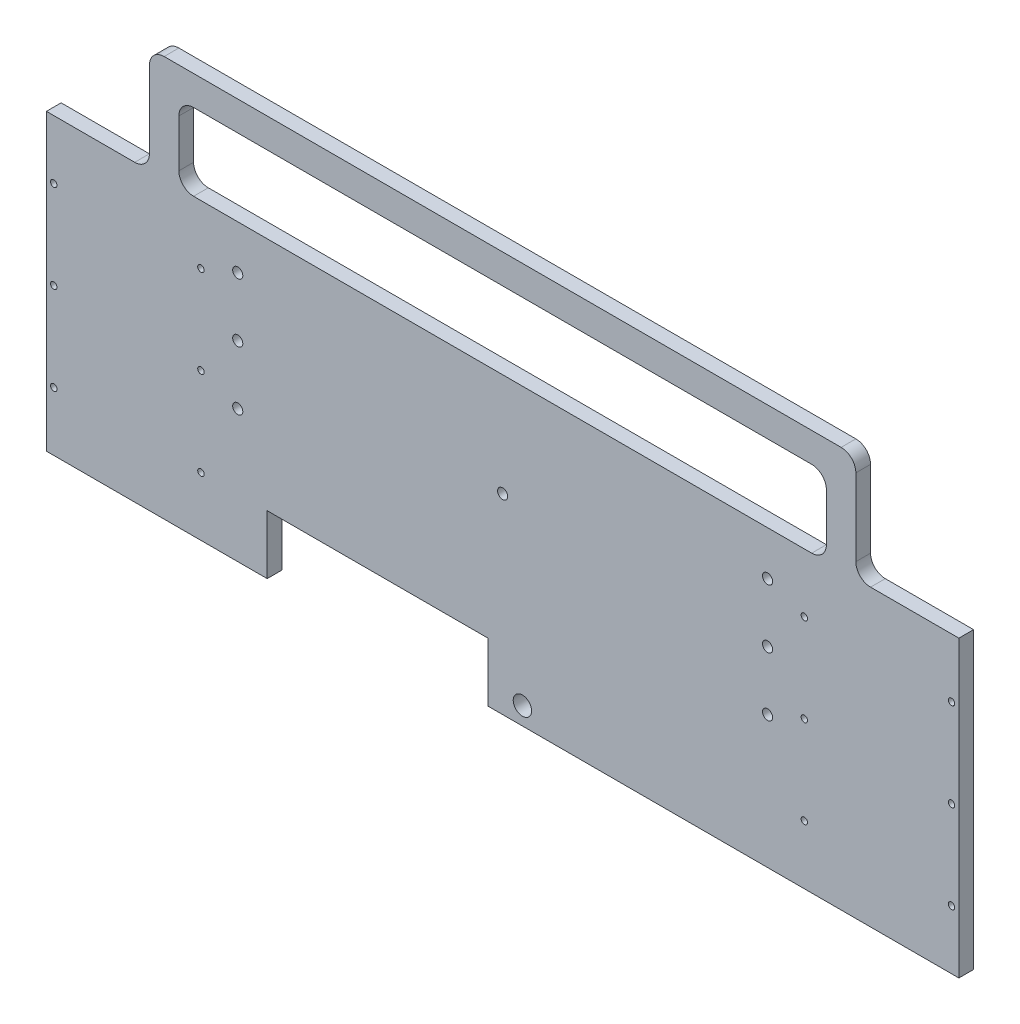
SolidWorks part; units mm, degrees
material "6061-T6 (SS)"
ref_plane "Front Plane" through (0, 0, 0) normal (0, 0, 1) x (1, 0, 0)
ref_plane "Top Plane" through (0, 0, 0) normal (0, 1, 0) x (1, 0, 0)
ref_plane "Right Plane" through (0, 0, 0) normal (1, 0, 0) x (0, 0, -1)
sketch "Sketch1" plane through (0, 0, 0) normal (0, 0, 1) x (1, 0, 0)
  line L1 (-196.85, 63.5) -> (196.85, 63.5)
  line L2 (-196.85, 63.5) -> (-196.85, -63.5)
  line L3 (-196.85, -63.5) -> (196.85, -63.5)
  line L4 (196.85, 63.5) -> (196.85, -63.5)
  line L5 (-196.85, 63.5) -> (196.85, -63.5) construction
  line L6 (-196.85, -63.5) -> (196.85, 63.5) construction
  point P0 (0, 0)
  dimension "D1" = 127
  dimension "D2" = 393.7
extrude "Boss-Extrude1" add sketch "Sketch1" along normal blind 6.35
sketch "Sketch2" plane through (0, 0, 6.35) normal (0, 0, 1) x (1, 0, 0)
  line L0 (196.85, -63.5) -> (196.85, 63.5) construction
  line L1 (-91.44, 27.94) -> (91.44, 27.94) construction
  line L2 (-91.44, 27.94) -> (-91.44, -27.94) construction
  line L3 (-91.44, -27.94) -> (91.44, -27.94) construction
  line L4 (91.44, 27.94) -> (91.44, -27.94) construction
  line L5 (-91.44, 27.94) -> (91.44, -27.94) construction
  line L6 (-91.44, -27.94) -> (91.44, 27.94) construction
  line L7 (192.278, -48.26) -> (-192.278, -48.26) construction
  line L8 (192.278, -48.26) -> (192.278, -11.43) construction
  line L9 (192.278, -11.43) -> (-192.278, -11.43) construction
  line L10 (-192.278, -48.26) -> (-192.278, -11.43) construction
  line L11 (192.278, -48.26) -> (-192.278, -11.43) construction
  line L12 (192.278, -11.43) -> (-192.278, -48.26) construction
  line L13 (-196.85, -63.5) -> (196.85, -63.5) construction
  point P0 (0, 0)
  point P6 (0, -29.845)
  point P13 (91.44, 0)
  point P19 (-91.44, 0)
  dimension "D1" = 182.88
  dimension "D2" = 55.88
  dimension "D3" = 4.572
  dimension "D4" = 36.83
  dimension "D5" = 15.24
sketch "Sketch10" plane through (0, 0, 6.35) normal (0, 0, 1) x (1, 0, 0)
  line L0 (196.85, 63.5) -> (-196.85, 63.5) construction
  line L1 (-152.4, 63.5) -> (-139.7, 63.5)
  line L2 (-152.4, 63.5) -> (-152.4, 109.383)
  line L3 (-152.4, 109.383) -> (-146.05, 109.383)
  line L4 (-139.7, 63.5) -> (-139.7, 96.683)
  line L5 (-196.85, 63.5) -> (-196.85, -63.5) construction
  line L6 (-152.4, 109.383) -> (152.4, 109.383)
  line L7 (-152.4, 109.383) -> (-152.4, 96.683)
  line L8 (-139.7, 96.683) -> (139.7, 96.683)
  line L9 (0, 109.383) -> (0, 96.683)
  line L10 (139.7, 63.5) -> (139.7, 96.683)
  line L11 (152.4, 63.5) -> (139.7, 63.5)
  line L12 (152.4, 63.5) -> (152.4, 109.383)
  line M12 (196.85, 63.5) -> (-196.85, 63.5)
  dimension "D1" = 12.7
  dimension "D2" = 12.7
  dimension "D3" = 152.4
  dimension "D4" = 44.45
extrude "Boss-Extrude2" add sketch "Sketch10" against normal blind 6.35 contours L9 L6 L3 L2 L4 L8 M12 | L12 L6 L9 L8 L10 M12
fillet "Fillet1" radius 6.35 8 edges at (152.4, 109.383, 3.175) (-152.4, 109.383, 3.175) (-152.4, 63.5, 3.175) (152.4, 63.5, 3.175) (139.7, 96.683, 3.175) (139.7, 63.5, 3.175) (-139.7, 63.5, 3.175) (-139.7, 96.683, 3.175)
sketch "Sketch9" plane through (0, 0, 6.35) normal (0, 0, 1) x (1, 0, 0)
  line L103 (-196.85, -63.5) -> (196.85, -63.5) construction
  point P113 (0, -63.5)
sketch "Sketch11" plane through (0, 0, 6.35) normal (0, 0, 1) x (1, 0, 0)
  line L0 (-196.85, -63.5) -> (196.85, -63.5) construction
  line L1 (-101.6, -63.5) -> (-6.35, -63.5)
  line L2 (-101.6, -63.5) -> (-101.6, -38.1)
  line L3 (-101.6, -38.1) -> (-6.35, -38.1)
  line L4 (-6.35, -63.5) -> (-6.35, -38.1)
  line L5 (-196.85, 63.5) -> (-196.85, -63.5) construction
  line L6 (196.85, -63.5) -> (196.85, 63.5) construction
  dimension "D1" = 25.4
  dimension "D2" = 95.25
  dimension "D3" = 203.2
extrude "Cut-Extrude1" cut sketch "Sketch11" against normal through all
sketch "Sketch12" plane through (0, 0, 6.35) normal (0, 0, 1) x (1, 0, 0)
  line L0 (-6.35, -63.5) -> (-6.35, -38.1) construction
  line L1 (-6.35, -63.5) -> (196.85, -63.5) construction
  point P0 (8.5349, -55.88)
  dimension "D1" = 14.8849
  dimension "D2" = 7.62
hole_wizard "5/16 (0.3125) Diameter Hole1" positions "Sketch13" profile "Sketch14" hole size "5/16" standard "ANSI Inch" end condition through all
sketch "Sketch13" plane through (0, 0, 6.35) normal (0, 0, 1) x (1, 0, 0)
  point P0 (8.5349, -55.88)
sketch "Sketch14" plane through (8.5349, -55.88, 6.35) normal (1, 0, 0) x (0, -1, 0)
  line L0 (0, 0) -> (0, 6.35)
  line L1 (0, 6.35) -> (3.9687, 6.35)
  line L2 (3.9687, 6.35) -> (3.9687, 0)
  line L5 (3.9687, 0) -> (0, 0)
  line L11 (0, -6.35) -> (0, 107.95) construction
  dimension "Thru Hole Dia." = 7.9375
  dimension "Thru Hole Depth" = 6.35
sketch "Sketch15" plane through (0, 0, 6.35) normal (0, 0, 1) x (1, 0, 0)
  line L1 (-196.85, 63.5) -> (-196.85, -63.5) construction
  line L2 (-196.85, -63.5) -> (-101.6, -63.5) construction
  line L3 (196.85, -63.5) -> (196.85, 63.5) construction
  line L4 (-6.35, -63.5) -> (196.85, -63.5) construction
  point P0 (-114.3, -57.15)
  point P1 (-114.3, -31.75)
  point P2 (-114.3, -6.35)
  point P3 (-114.3, 19.05)
  point P8 (-114.3, 44.45)
  point P9 (114.3, -57.15)
  point P11 (114.3, -31.75)
  point P12 (114.3, -6.35)
  point P13 (114.3, 19.05)
  point P14 (114.3, 44.45)
  dimension "D1" = 82.55
  dimension "D2" = 6.35
  dimension "D3" = 25.4
  dimension "D4" = 25.4
  dimension "D5" = 25.4
  dimension "D6" = 25.4
  dimension "D7" = 25.4
  dimension "D8" = 25.4
  dimension "D9" = 25.4
  dimension "D10" = 25.4
  dimension "D11" = 82.55
  dimension "D12" = 6.35
hole_wizard "11/64 (0.17188) Diameter Hole1" positions "Sketch16" profile "Sketch17" hole size "11/64" standard "ANSI Inch" end condition through all
sketch "Sketch16" plane through (0, 0, 6.35) normal (0, 0, 1) x (1, 0, 0)
  point P0 (-114.3, 44.45)
  point P3 (-114.3, 19.05)
  point P6 (-114.3, -6.35)
  point P12 (114.3, 44.45)
  point P15 (114.3, 19.05)
  point P18 (114.3, -6.35)
sketch "Sketch17" plane through (-114.3, 44.45, 6.35) normal (1, 0, 0) x (0, -1, 0)
  line L0 (0, 0) -> (0, 6.35)
  line L1 (0, 6.35) -> (2.1829, 6.35)
  line L2 (2.1829, 6.35) -> (2.1829, 0)
  line L5 (2.1829, 0) -> (0, 0)
  line L11 (0, -6.35) -> (0, 107.95) construction
  dimension "Thru Hole Dia." = 4.3658
  dimension "Thru Hole Depth" = 6.35
sketch "Sketch18" plane through (0, 0, 6.35) normal (0, 0, 1) x (1, 0, 0)
  line L0 (-196.85, 63.5) -> (-196.85, -63.5) construction
  line L1 (-158.75, 63.5) -> (-196.85, 63.5) construction
  line L3 (196.85, -63.5) -> (196.85, 63.5) construction
  line L4 (196.85, 63.5) -> (158.75, 63.5) construction
  line L5 (133.35, 63.5) -> (-133.35, 63.5) construction
  point P0 (-193.675, 38.1)
  point P1 (-193.675, 0)
  point P2 (-193.675, -38.1)
  point P7 (193.675, 38.1)
  point P8 (193.675, 0)
  point P9 (193.675, -38.1)
  point P14 (-130.175, 38.1)
  point P15 (-130.175, 0)
  point P16 (-130.175, -38.1)
  point P19 (130.175, 38.1)
  point P20 (130.175, 0)
  point P21 (130.175, -38.1)
  dimension "D1" = 3.175
  dimension "D2" = 25.4
  dimension "D3" = 38.1
  dimension "D4" = 38.1
  dimension "D5" = 3.175
  dimension "D6" = 25.4
  dimension "D7" = 38.1
  dimension "D8" = 38.1
  dimension "D9" = 66.675
  dimension "D10" = 25.4
  dimension "D11" = 38.1
  dimension "D12" = 38.1
  dimension "D13" = 66.675
  dimension "D14" = 25.4
  dimension "D15" = 38.1
  dimension "D16" = 38.1
hole_wizard "#35 (0.11) Diameter Hole1" positions "Sketch19" profile "Sketch20" hole size "#35" standard "ANSI Inch"
sketch "Sketch19" plane through (0, 0, 6.35) normal (0, 0, 1) x (1, 0, 0)
  point P0 (-193.675, 38.1)
  point P3 (-130.175, 38.1)
  point P6 (-130.175, 0)
  point P9 (-193.675, 0)
  point P12 (-193.675, -38.1)
  point P15 (-130.175, -38.1)
  point P18 (130.175, -38.1)
  point P21 (193.675, -38.1)
  point P24 (193.675, 0)
  point P27 (193.675, 38.1)
  point P30 (130.175, 38.1)
  point P33 (130.175, 0)
sketch "Sketch20" plane through (-193.675, 38.1, 6.35) normal (1, 0, 0) x (0, -1, 0)
  line L0 (0, 0) -> (0, 9.7294)
  line L1 (0, 9.7294) -> (1.397, 8.89)
  line L2 (1.397, 8.89) -> (1.397, 0)
  line L5 (1.397, 0) -> (0, 0)
  line L10 (0, 9.7294) -> (-1.397, 8.89) construction
  line L11 (0, -6.35) -> (0, 107.95) construction
  dimension "Hole Dia." = 2.794
  dimension "Hole Depth" = 8.89
  dimension "Drill Angle" = 118
sketch "Sketch21" plane through (0, 0, 6.35) normal (0, 0, 1) x (1, 0, 0)
  line L0 (133.35, 63.5) -> (-133.35, 63.5) construction
  line L1 (-196.85, 63.5) -> (-196.85, -63.5) construction
  point P0 (0, 19.05)
  dimension "D1" = 44.45
  dimension "D2" = 196.85
hole_wizard "11/64 (0.17188) Diameter Hole2" positions "Sketch22" profile "Sketch23" hole size "11/64" standard "ANSI Inch"
sketch "Sketch22" plane through (0, 0, 6.35) normal (0, 0, 1) x (1, 0, 0)
  point P0 (0, 19.05)
sketch "Sketch23" plane through (0, 19.05, 6.35) normal (1, 0, 0) x (0, -1, 0)
  line L0 (0, 0) -> (0, 10.2016)
  line L1 (0, 10.2016) -> (2.1829, 8.89)
  line L2 (2.1829, 8.89) -> (2.1829, 0)
  line L5 (2.1829, 0) -> (0, 0)
  line L10 (0, 10.2016) -> (-2.1829, 8.89) construction
  line L11 (0, -6.35) -> (0, 107.95) construction
  dimension "Hole Dia." = 4.3658
  dimension "Hole Depth" = 8.89
  dimension "Drill Angle" = 118
